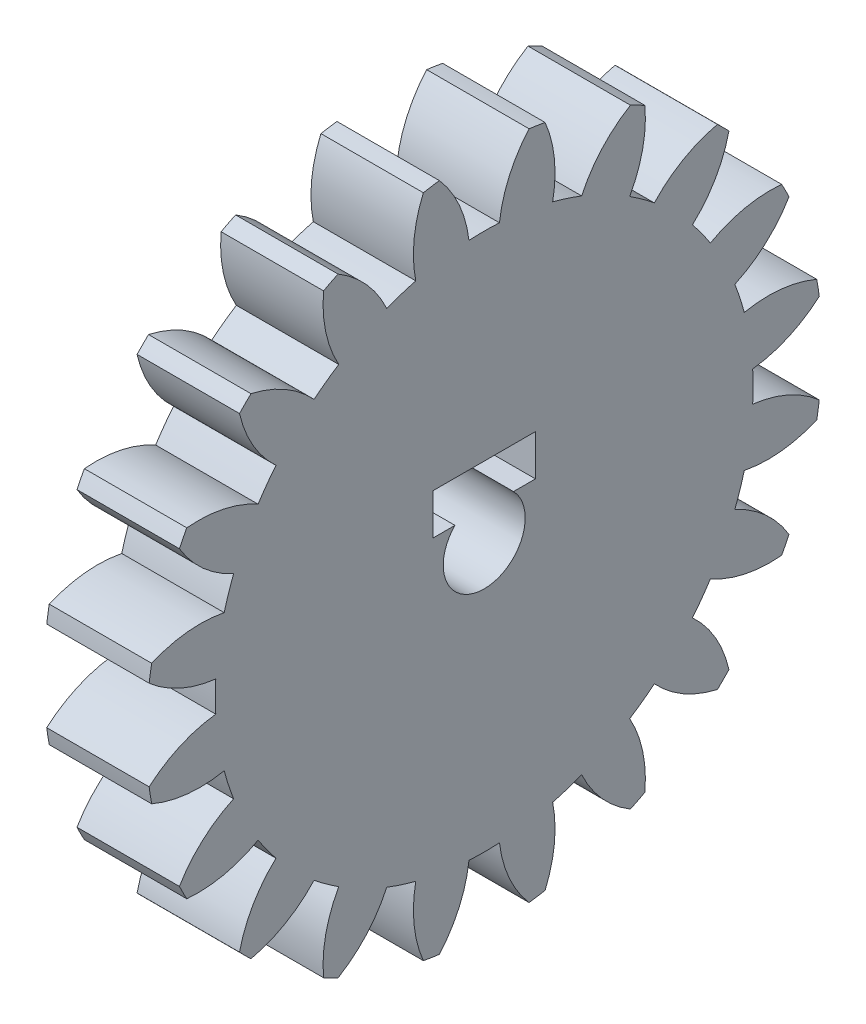
SolidWorks part; units mm, degrees
ref_plane "Plane1" through (0, 0, 0) normal (0, 0, 1) x (1, 0, 0)
ref_plane "Plane2" through (0, 0, 0) normal (0, 1, 0) x (1, 0, 0)
ref_plane "Plane3" through (0, 0, 0) normal (1, 0, 0) x (0, 0, -1)
sketch "HoldingSke" plane through (0, 0, 0) normal (0, 1, 0) x (1, 0, 0)
  line L0 (0, 0) -> (0.6265, -0.228)
  line L1 (-15, 0) -> (100, 0) construction
  line L2 (0, 0) -> (-2.1039, 2.3779)
  line L3 (0, 0) -> (-11.863, 4.5341)
  line L4 (0, 0) -> (8.1152, 2.9537)
  line L5 (0, 0) -> (-46.8476, -17.4728)
  line L6 (0, 0) -> (-4.1448, -2.7965)
  line L7 (-2.1039, 2.3779) -> (8.6586, 51.2059)
  line L8 (-76.2, 54.61) -> (-75.5, 54.61)
  line L9 (-71.009, 38.7566) -> (-53.1078, 45.2721)
  line L10 (-76.2, 71.12) -> (104.1128, 71.12)
  line L11 (0, 0) -> (-5, 0)
  line L12 (-76.2, 101.6) -> (-76.147, 101.6)
  line L13 (24.9733, 27.94) -> (52.9518, 28.4284)
  line L14 (24.9733, 27.94) -> (24.9743, 27.94)
  line L15 (24.9733, 27.94) -> (100.4006, 29.5858)
  line L16 (-63.627, -1.5) -> (-12.827, -1.5)
  circle A0 centre (0, 0) radius 2
  circle A1 centre (0, 0) radius 13.124
  circle A2 centre (0, 0) radius 37.5
  circle A3 centre (0, 0) radius 2
  dimension "MHD" = 26.248
  dimension "Hub_dia" = 75
  dimension "Bore" = 4
  dimension "MBD" = 4
  dimension "Num_teeth" = 20
  dimension "Pitch" = 0.6667
  dimension "Overall_len" = 50
  dimension "Show_teeth" = 20
  dimension "Thickness" = 5
  dimension "OAL" = 50.0001
  dimension "T_dim" = 0.7
  dimension "Ap" = 20
  dimension "H" = 19.05
  dimension "Pitch_radius" = 180.3128
  dimension "Width" = 5
  dimension "Backlash" = 0.053
  dimension "Addendum_fac" = 1
  dimension "Dedendum_fac" = 1.25
  dimension "Clearance_fac" = 0.25
  dimension "Dedendum_add" = 0.001
  dimension "Module" = 1.5
sketch "BasProSke" plane through (0, 0, 0) normal (0, 1, 0) x (1, 0, 0)
  line L0 (-10, 0) -> (60, 0) construction
  line L1 (0, 0) -> (0, 16.5)
  line L2 (0, 0) -> (5, 0)
  line L3 (5, 0) -> (5, 16.5)
  line L4 (5, 16.5) -> (0, 16.5)
  dimension "Thickness" = 5
  dimension "Diameter" = 33
revolve "Base-Revolve" add sketch "BasProSke" angle 360 about L0
sketch "TooCutSke" plane through (0, 0, 0) normal (1, 0, 0) x (0, 0, -1)
  line L1 (0, 0) -> (0, 107) construction
  line L2 (0, 0) -> (-1.2696, 14.9462) construction
  line L3 (0, 0) -> (-4.6808, 29.5532) construction
  line L4 (-1.2696, 14.9462) -> (-2.3404, 14.7766) construction
  arc A0 (0.7438, 13.1029) -> (-0.7438, 13.1029) centre (0, 0) ccw
  arc A1 (2.21, 16.377) -> (-2.21, 16.377) centre (0, 0) ccw
  circle A2 centre (0, 0) radius 15 construction
  circle A3 centre (0, 0) radius 14.0954 construction
  arc A4 (-0.7438, 13.1029) -> (-2.21, 16.377) centre (-6.7025, 12.3999) ccw
  arc A5 (2.21, 16.377) -> (0.7438, 13.1029) centre (6.7025, 12.3999) ccw
  dimension "Root_dia" = 26.248
  dimension "Overcut_dia" = 33.0508
  dimension "Pitch_dia" = 30
  dimension "Base_dia" = 28.1908
  dimension "Flank_rad" = 6
  dimension "Half_ang" = 9
  dimension "Half_CT" = 1.0841
extrude "ToothCut" cut sketch "TooCutSke" along normal through all
fillet "Breaks" [suppressed] radius 0.03
fillet "RootFillets" [suppressed] radius 0.376
pattern_circular "TeethCuts" count 20 every 18 about axis through (-10, 0, 0) along (1, 0, 0) of "ToothCut", "RootFillets", "Breaks"
sketch "HubNeaOneSke" plane through (0, 0, 0) normal (-1, 0, 0) x (0, 0, 1)
  circle A0 centre (0, 0) radius 13.124
  dimension "Diameter" = 26.248
extrude "HubNearOne" [suppressed] add sketch "HubNeaOneSke" along normal blind 45.0001
sketch "HubNeaBotSke" plane through (0, 0, 0) normal (-1, 0, 0) x (0, 0, 1)
  circle A0 centre (0, 0) radius 13.124
  dimension "Diameter" = 26.248
extrude "HubNearBoth" [suppressed] add sketch "HubNeaBotSke" along normal blind 22.5
ref_plane "FarPln" through (5, 0, 0) normal (1, 0, 0) x (0, 0, -1)
sketch "HubFarSke" plane through (5, 0, 0) normal (1, 0, 0) x (0, 0, -1)
  circle A0 centre (0, 0) radius 13.124
  dimension "Diameter" = 26.248
extrude "HubFar" [suppressed] add sketch "HubFarSke" along normal blind 22.5
sketch "BorSke" plane through (0, 0, 0) normal (1, 0, 0) x (0, 0, -1)
  circle A0 centre (0, 0) radius 2
  dimension "Diameter" = 4
extrude "Bore" cut sketch "BorSke" along normal mid plane 100.0001
sketch "KeySke" plane through (0, 0, 0) normal (1, 0, 0) x (0, 0, -1)
  line L0 (-0.8, 0) -> (-0.8, 2.7)
  line L1 (-0.8, 2.7) -> (0.8, 2.7)
  line L2 (0.8, 2.7) -> (0.8, 0)
  line L3 (0, 0) -> (0, 34) construction
  line L4 (-0.8, 0) -> (0.8, 0)
  dimension "Offset" = 2.7
  dimension "Width" = 1.6
extrude "Keyway" [suppressed] cut sketch "KeySke" along normal mid plane 100.0001
pattern_circular "Keyway2" [suppressed] count 2 every 90 about axis through (-10, 0, 0) along (1, 0, 0)
sketch "Sketch1" plane through (5, 0, 0) normal (1, 0, 0) x (0, 0, -1)
  line L1 (-1.4283, 1.4) -> (-2.5, 1.4)
  line L2 (-2.5, 1.4) -> (-2.5, 3.4)
  line L3 (-2.5, 3.4) -> (2.5, 3.4)
  line L4 (2.5, 3.4) -> (2.5, 1.4)
  line L5 (2.5, 1.4) -> (1.4283, 1.4)
  arc A0 (1.4283, 1.4) -> (-1.4283, 1.4) centre (0, 0) ccw
  point P5 (0, 3.4)
  dimension "D2" = 4
  dimension "D3" = 5
  dimension "D4" = 2
extrude "Cut-Extrude1" cut sketch "Sketch1" against normal blind 10
equation "' \"Module@HoldingSke\" = 6.35"
equation "' \"Num_teeth@HoldingSke\" = 12"
equation "' \"Ap@HoldingSke\" =  20"
equation "' \"Ap@HoldingSke\" = 20"
equation "' \"Width@HoldingSke\" = 0.5 * 25.4"
equation "' \"Hub_dia@HoldingSke\"= 1 * 25.4"
equation "' \"Hub_dia@HoldingSke\" = 1 * 25.4"
equation "' \"Overall_len@HoldingSke\" = 1.0 * 25.4"
equation "' \"Bore@HoldingSke\" = 0.75 * 25.4"
equation "' \"T_dim@HoldingSke\" = 0.1 * 25.4"
equation "' \"Width@KeySke\" = 0.25 * 25.4"
equation "' \"Show_teeth@HoldingSke\" = 13"
equation "' \"Backlash@HoldingSke\" = 0.009 * 25.4"
equation "' \"Addendum_fac@HoldingSke\" = 1.0"
equation "' \"Dedendum_fac@HoldingSke\" = 1.25"
equation "' \"Dedendum_add@HoldingSke\" = 0.00005 * 25.4"
equation "' \"Clearance_fac@HoldingSke\" = 0.25"
equation "\"Pitch@HoldingSke\" = 1 / \"Module@HoldingSke\""
equation "\"Overcut_dia@TooCutSke\" = (\"Num_teeth@HoldingSke\" + 2 * \"Addendum_fac@HoldingSke\") / \"Pitch@HoldingSke\" + 0.002 * 25.4"
equation "\"Pitch_dia@TooCutSke\" = \"Num_teeth@HoldingSke\" / \"Pitch@HoldingSke\""
equation "\"Base_dia@TooCutSke\" = \"Num_teeth@HoldingSke\" / \"Pitch@HoldingSke\" * cos((\"Ap@HoldingSke\"  * 3.14159265 / 180))"
equation "\"Root_dia@TooCutSke\" = (\"Num_teeth@HoldingSke\" + 2) / \"Pitch@HoldingSke\" - 2 * (\"Addendum_fac@HoldingSke\" + \"Dedendum_fac@HoldingSke\") / \"Pitch@HoldingSke\" - \"Dedendum_add@HoldingSke\" * 2"
equation "\"Half_ang@TooCutSke\" = 180 / \"Num_teeth@HoldingSke\""
equation "\"Half_CT@TooCutSke\" = \"Num_teeth@HoldingSke\" / \"Pitch@HoldingSke\" * sin((3.14159265 / 2 / \"Num_teeth@HoldingSke\")) / 2 - 7 * \"Backlash@HoldingSke\" / 4"
equation "\"Flank_rad@TooCutSke\" = \"Num_teeth@HoldingSke\" / \"Pitch@HoldingSke\" / 5"
equation "\"Radius@RootFillets\" = \"Clearance_fac@HoldingSke\" / \"Pitch@HoldingSke\" + \"Dedendum_add@HoldingSke\""
equation "\"Break_rad@Breaks\" = 0.02 / \"Pitch@HoldingSke\""
equation "\"Thickness@HoldingSke\" = \"Width@HoldingSke\""
equation "\"OAL@HoldingSke\" = \"Thickness@HoldingSke\""
equation "\"MHD@HoldingSke\" = (\"Num_teeth@HoldingSke\" + 2) / \"Pitch@HoldingSke\" - 2 * (\"Addendum_fac@HoldingSke\" + \"Dedendum_fac@HoldingSke\")  / \"Pitch@HoldingSke\" - \"Dedendum_add@HoldingSke\" * 2"
equation "\"MBD@HoldingSke\" = (\"Num_teeth@HoldingSke\" + 2) / \"Pitch@HoldingSke\" - 2 * (\"Addendum_fac@HoldingSke\" + \"Dedendum_fac@HoldingSke\")  / \"Pitch@HoldingSke\" - \"Dedendum_add@HoldingSke\" * 2 - 0.002 * 25.4"
equation "\"MHD@HoldingSke\" = ((sgn( \"MHD@HoldingSke\" - \"Hub_dia@HoldingSke\" )-1)*( \"MHD@HoldingSke\" - \"Hub_dia@HoldingSke\" ))/-2+ \"Hub_dia@HoldingSke\""
equation "\"MBD@HoldingSke\" = ((sgn( \"MBD@HoldingSke\" - \"Bore@HoldingSke\" )-1)*( \"MBD@HoldingSke\" - \"Bore@HoldingSke\" ))/-2+ \"Bore@HoldingSke\""
equation "\"OAL@HoldingSke\" = ((sgn( \"OAL@HoldingSke\" - \"Overall_len@HoldingSke\" )+1)*( \"OAL@HoldingSke\" - \"Overall_len@HoldingSke\" ))/2 + \"Overall_len@HoldingSke\" + 0.000002 * 25.4"
equation "\"Num_teeth@TeethCuts\" = int( \"Show_teeth@HoldingSke\" ) + 1"
equation "\"Num_teeth@TeethCuts\" = ((sgn( \"Num_teeth@TeethCuts\" - \"Num_teeth@HoldingSke\" )-1)*( \"Num_teeth@TeethCuts\" - \"Num_teeth@HoldingSke\" ))/-2+ \"Num_teeth@HoldingSke\""
equation "\"Num_teeth@TeethCuts\" = ((sgn( \"Num_teeth@TeethCuts\" - 2.0)+1)*( \"Num_teeth@TeethCuts\" - 2.0))/2 +2.0"
equation "\"Angle@TeethCuts\" = 360.0 / \"Num_teeth@HoldingSke\""
equation "\"Diameter@BasProSke\" = (\"Num_teeth@HoldingSke\" + 2 * \"Addendum_fac@HoldingSke\") / \"Pitch@HoldingSke\""
equation "\"Thickness@BasProSke\"  = \"Thickness@HoldingSke\""
equation "' \"Fillet_rad@BasProSke\" =  \"Thickness@HoldingSke\" * 0.05"
equation "' \"Fillet_rad@BasProSke\" = \"Thickness@HoldingSke\" * 0.05"
equation "\"MHD@HoldingSke\" = ((sgn( \"MHD@HoldingSke\" - \"Root_dia@TooCutSke\" )-1)*( \"MHD@HoldingSke\" - \"Root_dia@TooCutSke\" ))/-2+ \"Root_dia@TooCutSke\""
equation "\"Diameter@HubNeaOneSke\" = \"MHD@HoldingSke\""
equation "\"Length@HubNearOne\" = \"OAL@HoldingSke\" - \"Thickness@BasProSke\""
equation "\"Diameter@HubNeaBotSke\" = \"MHD@HoldingSke\""
equation "\"Length@HubNearBoth\" = ( \"OAL@HoldingSke\" - \"Thickness@BasProSke\" ) / 2.0"
equation "\"Thickness@FarPln\" = \"Thickness@BasProSke\""
equation "\"Diameter@HubFarSke\" = \"MHD@HoldingSke\""
equation "\"Length@HubFar\" = ( \"OAL@HoldingSke\" - \"Thickness@BasProSke\" ) / 2.0"
equation "\"Diameter@BorSke\" = \"MBD@HoldingSke\""
equation "\"D1@Bore\" = \"OAL@HoldingSke\" * 2.0"
equation "\"D1@Keyway\" = \"OAL@HoldingSke\" * 2.0"
equation "\"Offset@KeySke\" = \"T_dim@HoldingSke\" + \"MBD@HoldingSke\" / 2.0"
